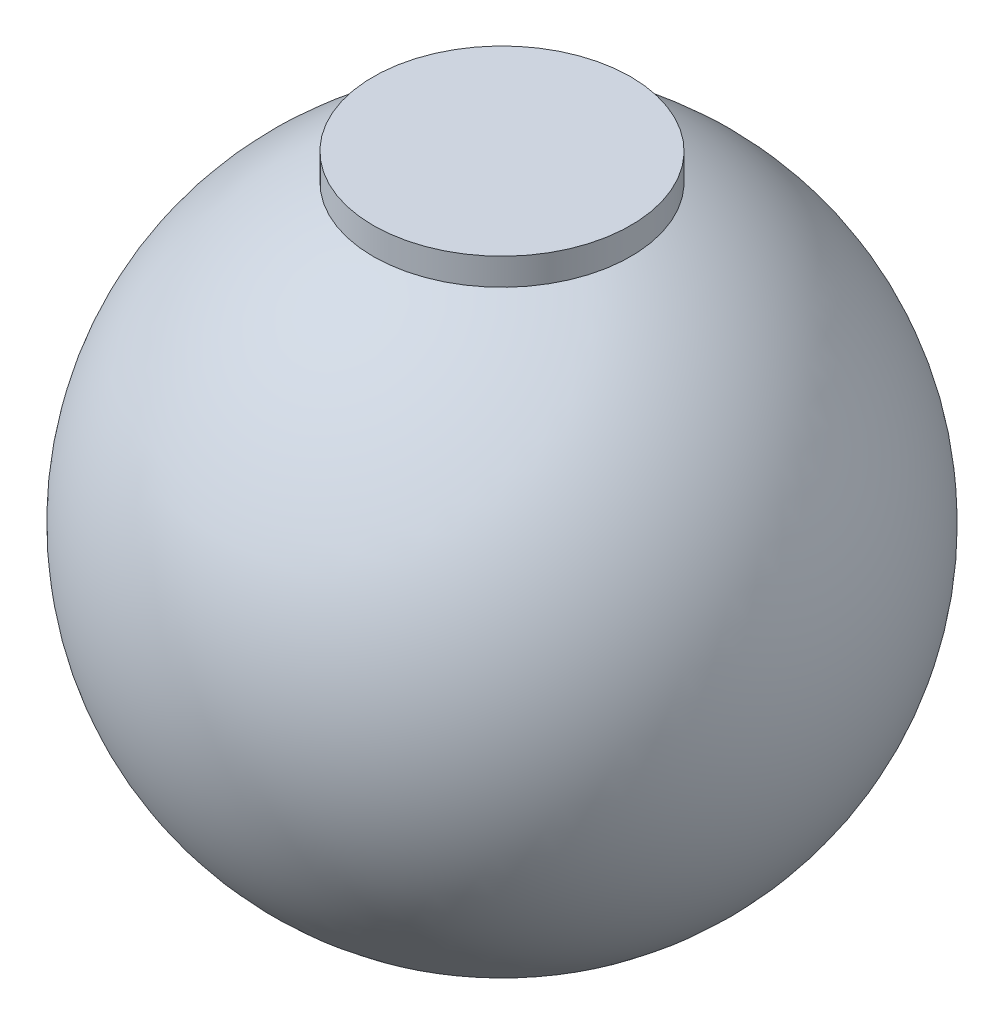
SolidWorks part; units mm, degrees
ref_plane "Front Plane" through (0, 0, 0) normal (0, 0, 1) x (1, 0, 0)
ref_plane "Top Plane" through (0, 0, 0) normal (0, 1, 0) x (1, 0, 0)
ref_plane "Right Plane" through (0, 0, 0) normal (1, 0, 0) x (0, 0, -1)
sketch "Sketch1" plane through (0, 0, 0) normal (0, 1, 0) x (1, 0, 0)
  line L0 (0, 0) -> (0, -200) construction
  line L1 (0, 0) -> (0, -200)
  arc A0 (0, 0) -> (0, -200) centre (0, -100) cw
revolve "Revolve1" add sketch "Sketch1" angle 360 about L0
sketch "Sketch3" plane through (0, 0, 0) normal (0, 1, 0) x (1, 0, 0)
  circle A0 centre (0, -100) radius 40
extrude "Boss-Extrude1" add sketch "Sketch3" along normal blind 100
